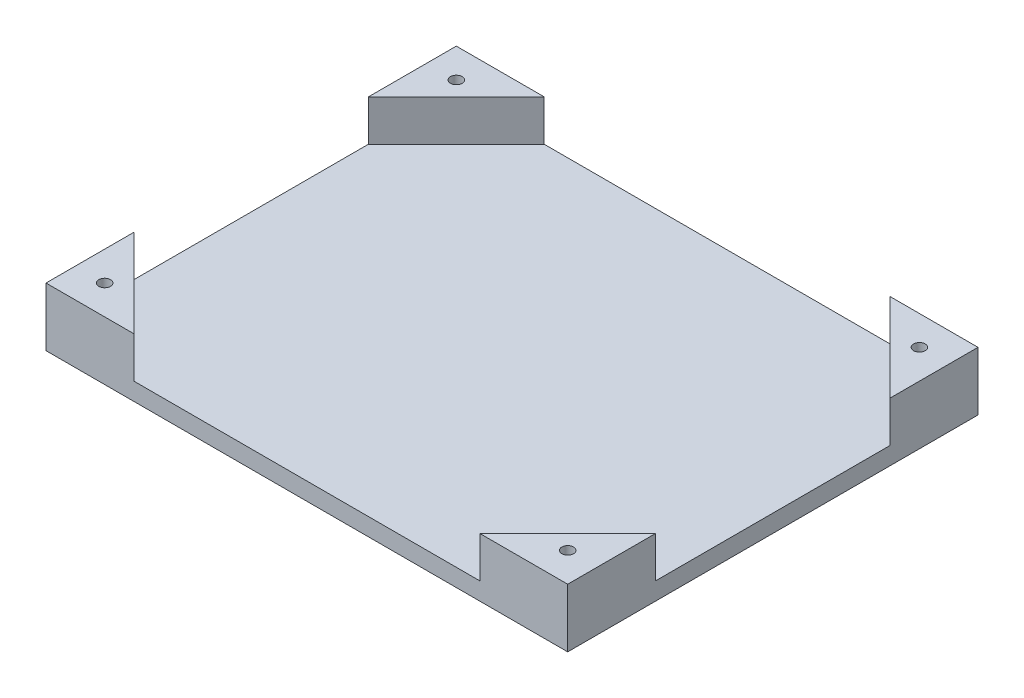
SolidWorks part; units mm, degrees
ref_plane "Front Plane" through (0, 0, 0) normal (0, 0, 1) x (1, 0, 0)
ref_plane "Top Plane" through (0, 0, 0) normal (0, 1, 0) x (1, 0, 0)
ref_plane "Right Plane" through (0, 0, 0) normal (1, 0, 0) x (0, 0, -1)
sketch "Sketch1" plane through (0, 0, 0) normal (0, 1, 0) x (1, 0, 0)
  line L1 (-44.5, -35) -> (44.5, -35)
  line L2 (-44.5, -35) -> (-44.5, 35)
  line L3 (-44.5, 35) -> (44.5, 35)
  line L4 (44.5, -35) -> (44.5, 35)
  line L5 (0, 35) -> (0, -35) construction
  line L6 (-44.5, 0) -> (44.5, 0) construction
  circle A0 centre (-39.5, 30) radius 1
  circle A1 centre (39.5, 30) radius 1
  circle A2 centre (39.5, -30) radius 1
  circle A3 centre (-39.5, -30) radius 1
  point P0 (0, 0)
  dimension "D3" = 2
  dimension "D1" = 89
  dimension "D2" = 70
  dimension "D4" = 5
  dimension "D5" = 5
extrude "Boss-Extrude1" add sketch "Sketch1" along normal blind 10
sketch "Sketch3" plane through (0, 10, 0) normal (0, 1, 0) x (1, 0, 0)
  line L0 (-44.5, -20) -> (-29.5, -35)
  line L1 (-44.5, 35) -> (-44.5, -35) construction
  line L2 (-44.5, -35) -> (44.5, -35) construction
  line L3 (-29.5, -35) -> (29.5, -35)
  line L4 (29.5, -35) -> (44.5, -20)
  line L5 (44.5, -35) -> (44.5, 35) construction
  line L6 (44.5, -20) -> (44.5, 20)
  line L7 (44.5, 20) -> (29.5, 35)
  line L8 (44.5, 35) -> (-44.5, 35) construction
  line L9 (29.5, 35) -> (-29.5, 35)
  line L10 (-29.5, 35) -> (-44.5, 20)
  line L11 (-44.5, 20) -> (-44.5, -20)
  line L12 (44.5, 20) -> (44.5, 27.0203) construction
  line L13 (-44.5, 20) -> (-44.5, 25.3065) construction
  dimension "D1" = 45
  dimension "D2" = 15
  dimension "D3" = 45
extrude "Cut-Extrude2" cut sketch "Sketch3" against normal blind 7
